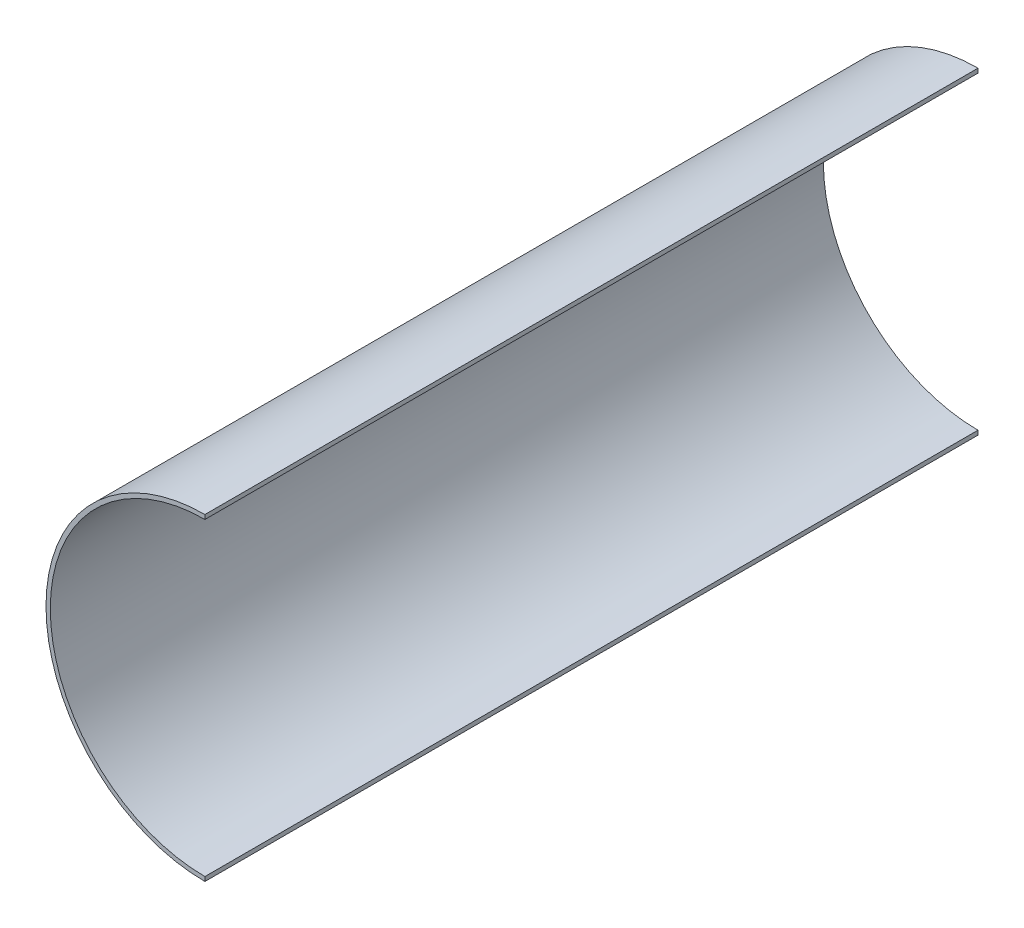
SolidWorks part; units mm, degrees
ref_plane "前视基准面" through (0, 0, 0) normal (0, 0, 1) x (1, 0, 0)
ref_plane "上视基准面" through (0, 0, 0) normal (0, 1, 0) x (1, 0, 0)
ref_plane "右视基准面" through (0, 0, 0) normal (1, 0, 0) x (0, 0, -1)
sketch "草图1" plane through (0, 0, 0) normal (0, 0, 1) x (1, 0, 0)
  circle A0 centre (0, 0) radius 18
  circle A1 centre (0, 0) radius 18.5
extrude "凸台-拉伸1" add sketch "草图1" along normal blind 90
sketch "草图2" plane through (0, 0, 0) normal (0, 0, -1) x (-1, 0, 0)
  line L0 (0, 0) -> (-6.6047, 0)
  line L1 (0, 0) -> (0, -7.5077)
sketch "草图3" plane through (0, 0, 90) normal (0, 0, 1) x (1, 0, 0)
  line L0 (0, 0) -> (0, -7.5077)
  line L1 (0, 0) -> (6.6047, 0)
ref_plane "基准面4" through (0, 0, 0) normal (1, 0, 0) x (0, 0, -1)
sketch "草图4" plane through (0, 0, 0) normal (0, 0, -1) x (-1, 0, 0)
  line L0 (0, 22.8841) -> (0, -22.8841) construction
  line L1 (0, 20.4292) -> (-20.5523, 20.4292)
  line L2 (0, 20.4292) -> (0, -21.4413)
  line L3 (0, -21.4413) -> (-20.5523, -21.4413)
  line L4 (-20.5523, 20.4292) -> (-20.5523, -21.4413)
extrude "切除-拉伸1" cut sketch "草图4" against normal blind 90
